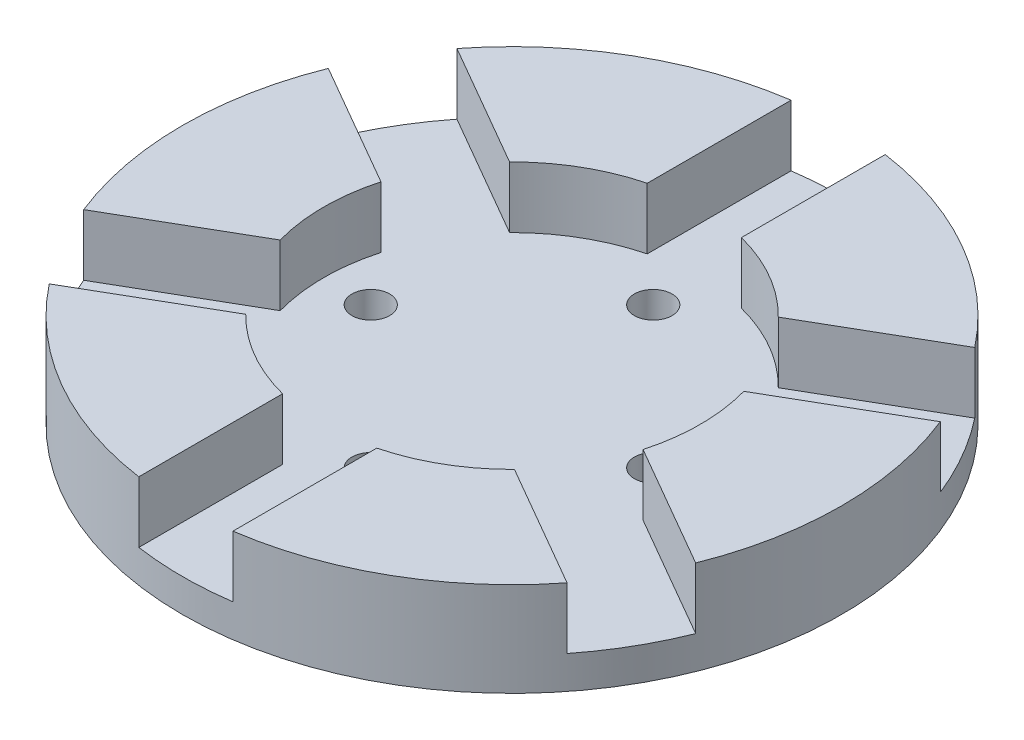
SolidWorks part; units mm, degrees
ref_plane "Front Plane" through (0, 0, 0) normal (0, 0, 1) x (1, 0, 0)
ref_plane "Top Plane" through (0, 0, 0) normal (0, 1, 0) x (1, 0, 0)
ref_plane "Right Plane" through (0, 0, 0) normal (1, 0, 0) x (0, 0, -1)
sketch "Sketch1" plane through (0, 0, 0) normal (0, 1, 0) x (1, 0, 0)
  circle A0 centre (0, 0) radius 35
  dimension "D1" = 70
extrude "Boss-Extrude1" add sketch "Sketch1" along normal blind 10
sketch "Sketch2" plane through (0, 10, 0) normal (0, 1, 0) x (1, 0, 0)
  circle A0 centre (0, 0) radius 15 construction
  circle A1 centre (0, 15) radius 2
  dimension "D1" = 4
  dimension "D2" = 30
extrude "Cut-Extrude1" cut sketch "Sketch2" against normal up to next
pattern_circular "CirPattern1" count 4 over 360 about axis through (0, 0, 0) along (0, 1, 0) of "Cut-Extrude1"
sketch "Sketch5" plane through (0, 0, 0) normal (0, 0, 1) x (1, 0, 0)
  line L0 (0, 0) -> (0, 16.3467) construction
  line L1 (-35, 0) -> (35, 0) construction
  line L2 (-5, 20.1012) -> (5, 20.1012)
  line L3 (-5, 20.1012) -> (-5, 3.5)
  line L4 (-5, 3.5) -> (5, 3.5)
  line L5 (5, 20.1012) -> (5, 3.5)
  line L6 (-5, 20.1012) -> (5, 3.5) construction
  line L7 (-5, 3.5) -> (5, 20.1012) construction
  point P3 (0, 11.8006)
  dimension "D1" = 3.5
  dimension "D2" = 10
extrude "Cut-Extrude2" cut sketch "Sketch5" against normal through all and the other way through all
pattern_circular "CirPattern2" count 3 over 360 about axis through (0, 0, 0) along (0, 1, 0) of "Cut-Extrude2"
sketch "Sketch6" plane through (0, 10, 0) normal (0, 1, 0) x (1, 0, 0)
  circle A0 centre (0, 0) radius 20
  dimension "D1" = 40
extrude "Cut-Extrude3" cut sketch "Sketch6" against normal up to surface (6.5 mm away) up to face at (0, 3.5, 0)
